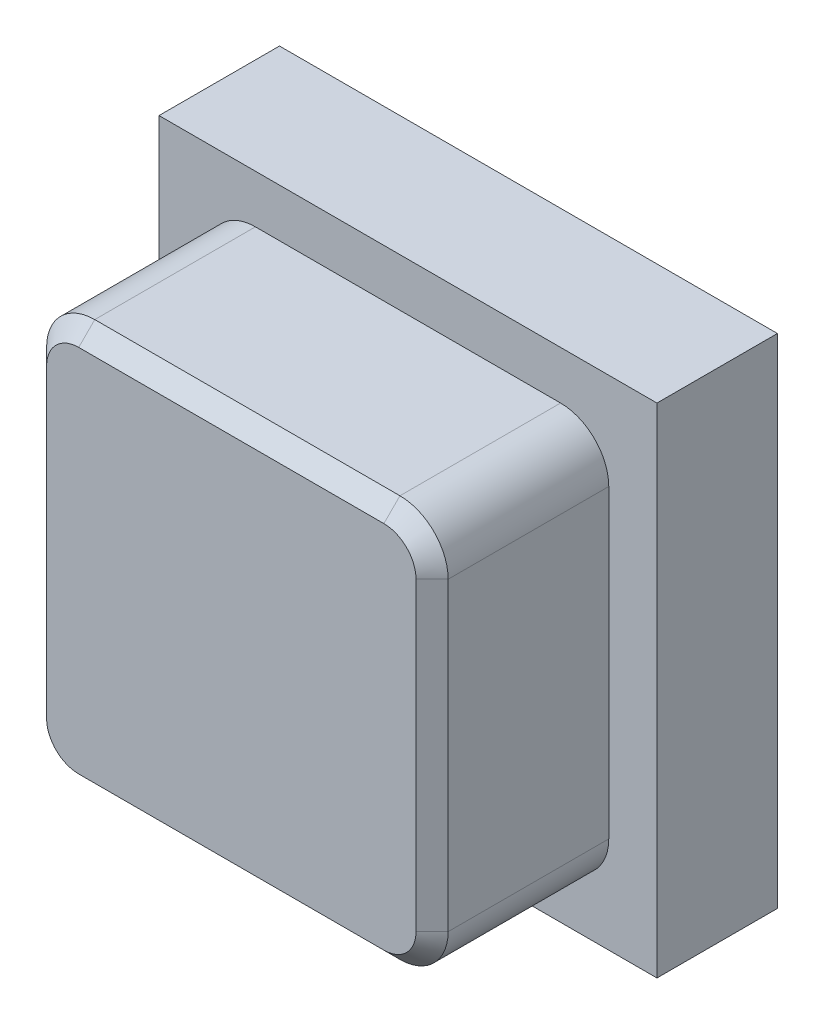
SolidWorks part; units mm, degrees
ref_plane "Спереди" through (0, 0, 0) normal (0, 0, 1) x (1, 0, 0)
ref_plane "Сверху" through (0, 0, 0) normal (0, 1, 0) x (1, 0, 0)
ref_plane "Справа" through (0, 0, 0) normal (1, 0, 0) x (0, 0, -1)
sketch "Эскиз1" plane through (0, 0, 0) normal (0, 0, 1) x (1, 0, 0)
  line L1 (0, 0) -> (10, 0)
  line L2 (0, 0) -> (0, -10)
  line L3 (0, -10) -> (10, -10)
  line L4 (10, 0) -> (10, -10)
  dimension "D1" = 10
extrude "Бобышка-Вытянуть1" add sketch "Эскиз1" along normal blind 4.4
sketch "Эскиз2" plane through (0, 0, 0) normal (0, 0, -1) x (-1, 0, 0)
  line L8 (1.2, -11.2) -> (1.2, 1.2)
  line L9 (1.2, 1.2) -> (-11.2, 1.2)
  line L10 (-11.2, 1.2) -> (-11.2, -11.2)
  line L11 (-11.2, -11.2) -> (1.2, -11.2)
  line L12 (1.2, -11.2) -> (1.2, 1.2)
  line L13 (1.2, 1.2) -> (-11.2, 1.2)
  line L14 (-11.2, 1.2) -> (-11.2, -11.2)
  line L15 (-11.2, -11.2) -> (1.2, -11.2)
  dimension "D1" = 1.2
extrude "Бобышка-Вытянуть2" add sketch "Эскиз2" along normal blind 3
sketch "Эскиз3" plane through (0, 0, -3) normal (0, 0, -1) x (-1, 0, 0)
  line L0 (-11.2, -11.2) -> (1.2, 1.2) construction
  circle A1 centre (-5, -5) radius 1.8
  dimension "D1" = 3.6
extrude "Вырез-Вытянуть1" cut sketch "Эскиз3" against normal up to surface (3 mm away) up to face at (5, -5, 0)
fillet "Скругление1" radius 1.2 4 edges at (10, 0, 2.2) (0, 0, 2.2) (0, -10, 2.2) (10, -10, 2.2)
chamfer "Фаска1" distance 0.4 angle 45 8 edges at (0, -5, 4.4) (0.3515, -9.6485, 4.4) (0.3515, -0.3515, 4.4) (5, -10, 4.4) (5, 0, 4.4) (9.6485, -9.6485, 4.4) (9.6485, -0.3515, 4.4) (10, -5, 4.4)
chamfer "Фаска2" distance 0.4 angle 45 1 edges at (3.2, -5, -3)
